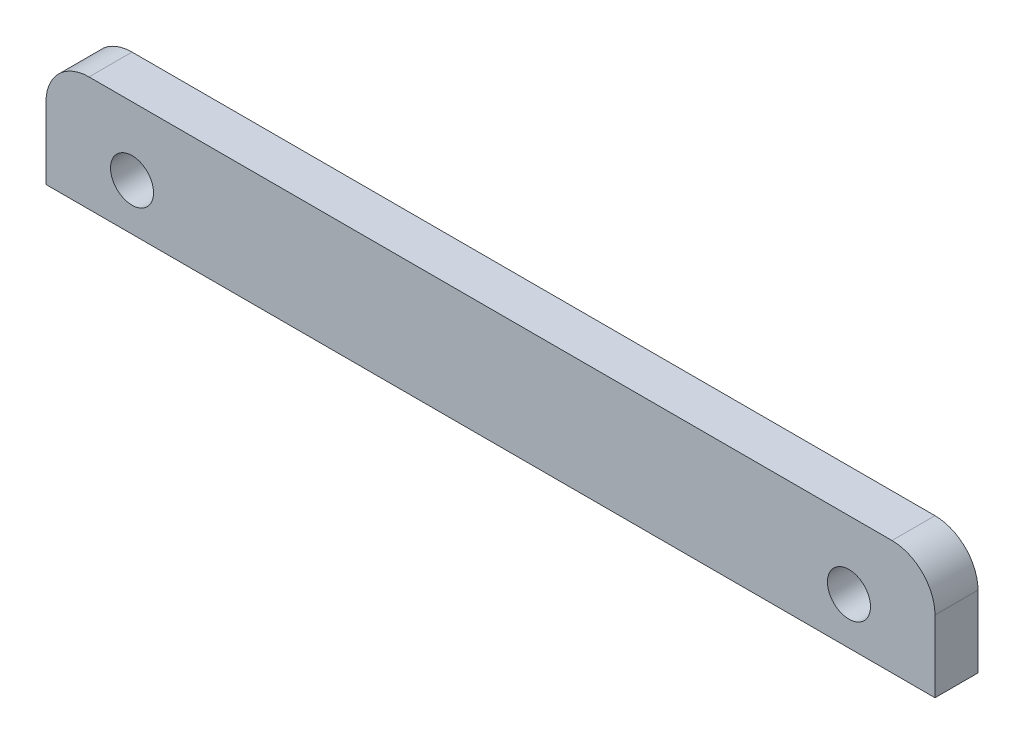
SolidWorks part; units mm, degrees
ref_plane "Front Plane" through (0, 0, 0) normal (0, 0, 1) x (1, 0, 0)
ref_plane "Top Plane" through (0, 0, 0) normal (0, 1, 0) x (1, 0, 0)
ref_plane "Right Plane" through (0, 0, 0) normal (1, 0, 0) x (0, 0, -1)
sketch "Sketch1" plane through (0, 0, 0) normal (0, 0, 1) x (1, 0, 0)
  line L1 (-28, 5.5) -> (28, 5.5)
  line L2 (-31, 2.5) -> (-31, -2.5)
  line L3 (-31, -2.5) -> (31, -2.5)
  line L4 (31, 2.5) -> (31, -2.5)
  line L5 (0, -2.5) -> (0, 5.5) construction
  line L6 (-31, 0) -> (31, 0) construction
  arc A0 (28, 5.5) -> (31, 2.5) centre (28, 2.5) cw
  arc A1 (-28, 5.5) -> (-31, 2.5) centre (-28, 2.5) ccw
  circle A2 centre (-25, 0.75) radius 1.5
  circle A3 centre (25, 0.75) radius 1.5
  point P0 (0, 0)
  point P9 (-31, 5.5)
  dimension "D3" = 3
  dimension "D1" = 62
  dimension "D2" = 8
extrude "Boss-Extrude1" add sketch "Sketch1" along normal blind 3
